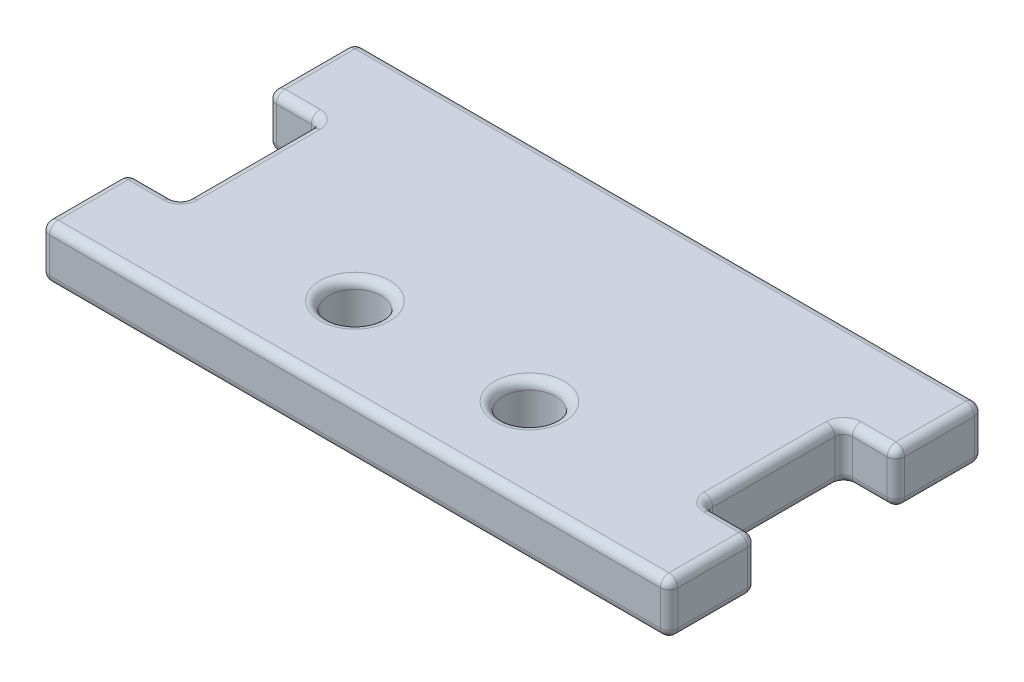
SolidWorks part; units mm, degrees
ref_plane "前视基准面" through (0, 0, 0) normal (0, 0, 1) x (1, 0, 0)
ref_plane "上视基准面" through (0, 0, 0) normal (0, 1, 0) x (1, 0, 0)
ref_plane "右视基准面" through (0, 0, 0) normal (1, 0, 0) x (0, 0, -1)
ref_plane "基准面1" through (0, -1.5, 0) normal (0, -1, 0) x (1, 0, 0)
sketch "草图1" plane through (0, -1.5, 0) normal (0, -1, 0) x (1, 0, 0)
  line L0 (18, -9) -> (18, -4)
  line L1 (18, -4) -> (15, -4)
  line L2 (15, -4) -> (15, 4)
  line L3 (15, 4) -> (18, 4)
  line L4 (18, 4) -> (18, 9)
  line L5 (18, 9) -> (-18, 9)
  line L6 (-18, 9) -> (-18, 4)
  line L7 (-18, 4) -> (-15, 4)
  line L8 (-15, 4) -> (-15, -4)
  line L9 (-15, -4) -> (-18, -4)
  line L10 (-18, -4) -> (-18, -9)
  line L11 (-18, -9) -> (18, -9)
  circle A0 centre (5, 4) radius 1.5
  circle A1 centre (-5, 4) radius 1.5
  dimension "D1" = 3
  dimension "D2" = 3
  dimension "D3" = 10
  dimension "D4" = 36
  dimension "D5" = 8
  dimension "D6" = 5
  dimension "D7" = 5
extrude "凸台-拉伸1" add sketch "草图1" against normal blind 3
fillet "圆角1" radius 0.5 38 edges at (15, 0, 4) (-16.5, -1.5, -4) (16.5, -1.5, 4) (15, -1.5, 0) (0, -1.5, 9) (18, 0, 9) (18, 0, 4) (18, -1.5, 6.5) (15, 0, -4) (16.5, -1.5, -4) (18, 0, -4) (18, -1.5, -6.5) (-18, 0, -4) (-18, -1.5, -6.5) (18, 0, -9) (-18, 0, -9) (0, -1.5, -9) (-18, 0, 9) (-18, -1.5, 6.5) (-18, 0, 4) (-16.5, -1.5, 4) (-15, 0, -4) (-15, 0, 4) (-15, -1.5, 0) (18, 1.5, -6.5) (16.5, 1.5, -4) (15, 1.5, 0) (16.5, 1.5, 4) (18, 1.5, 6.5) (0, 1.5, 9) (-18, 1.5, 6.5) (-16.5, 1.5, 4) (-15, 1.5, 0) (-16.5, 1.5, -4) (-18, 1.5, -6.5) (0, 1.5, -9) (5, 1.5, 5.5) (-5, 1.5, 5.5)
fillet "圆角2" radius 0.5 2 edges at (-5, -1.5, 5.5) (5, -1.5, 5.5)
